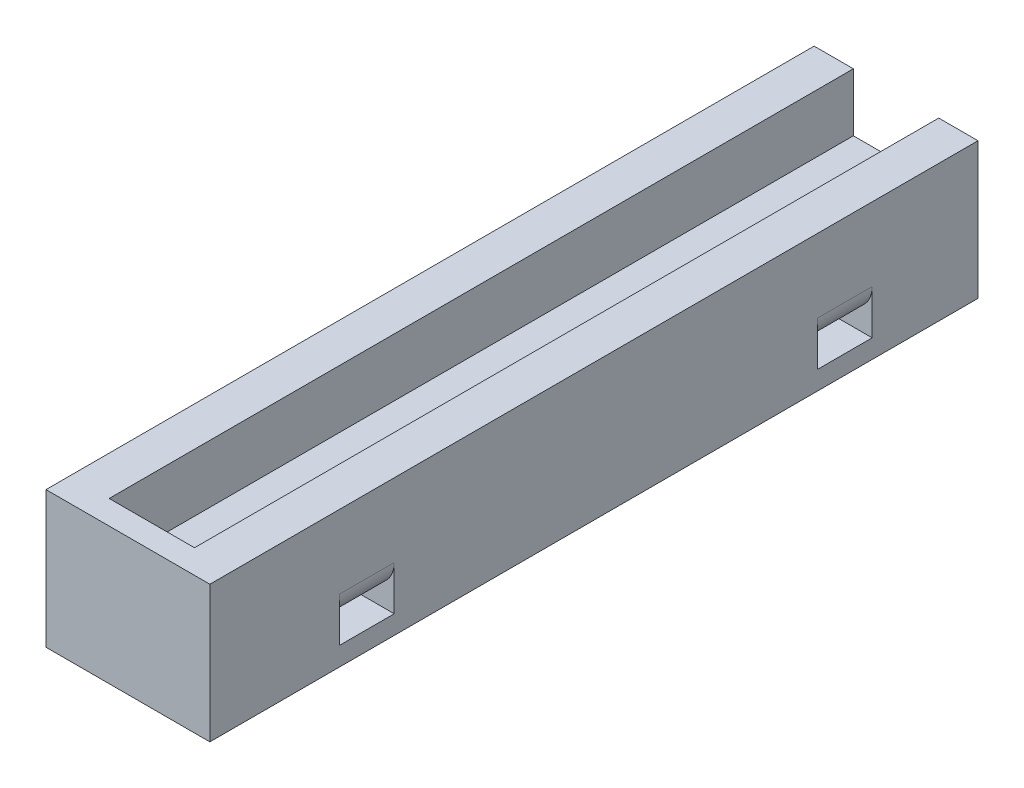
SolidWorks part; units mm, degrees
material "PLA"
ref_plane "Front Plane" through (0, 0, 0) normal (0, 0, 1) x (1, 0, 0)
ref_plane "Top Plane" through (0, 0, 0) normal (0, 1, 0) x (1, 0, 0)
ref_plane "Right Plane" through (0, 0, 0) normal (1, 0, 0) x (0, 0, -1)
sketch "Sketch1" plane through (0, 0, 0) normal (0, 0, 1) x (1, 0, 0)
  line L0 (-36, 5.6) -> (-26, 5.6) construction
  line L1 (-31, 5.6) -> (-31, 5.75) construction
  line L2 (0, 0) -> (-320, 0) construction
  line L3 (-37.25, 11.5) -> (-24.75, 11.5)
  line L4 (-37.25, 11.5) -> (-37.25, 0)
  line L5 (-37.25, 0) -> (-24.75, 0)
  line L6 (-24.75, 11.5) -> (-24.75, 0)
  line L7 (-37.25, 11.5) -> (-24.75, 0) construction
  line L8 (-37.25, 0) -> (-24.75, 11.5) construction
  line L10 (-24.75, 0) -> (-19, 0)
  line L11 (-24.75, 0) -> (-24.75, 20)
  line L12 (-24.75, 20) -> (-19, 20)
  line L13 (-19, 0) -> (-19, 20)
  line L14 (-37.25, 0) -> (-43, 0)
  line L15 (-37.25, 0) -> (-37.25, 20)
  line L16 (-37.25, 20) -> (-43, 20)
  line L17 (-43, 0) -> (-43, 20)
  dimension "D1" = 24
  dimension "D2" = 12.5
  dimension "D3" = 11.5
  dimension "D4" = 20
extrude "Boss-Extrude1" add sketch "Sketch1" along normal blind 109 contours L17 L14 L4 L15 L16 | L6 L3 L4 L5 | L10 L13 L12 L11 L6
sketch "Sketch2" plane through (0, 0, 109) normal (0, 0, 1) x (1, 0, 0)
  line L1 (-43, 20) -> (-19, 20)
  line L2 (-43, 20) -> (-43, 0)
  line L3 (-43, 0) -> (-19, 0)
  line L4 (-19, 20) -> (-19, 0)
extrude "Boss-Extrude2" add sketch "Sketch2" along normal blind 3.5
sketch "Sketch3" plane through (0, 0, 0) normal (0, 0, -1) x (-1, 0, 0)
  circle A0 centre (26, 5.6) radius 1.45 construction
  circle A1 centre (26, 5.6) radius 1.45 construction
  circle A2 centre (36, 5.6) radius 1.45 construction
  circle A3 centre (36, 5.6) radius 1.45 construction
  point P7 (26, 5.6)
  point P8 (36, 5.6)
hole_wizard "Ø2.5mm Dowel Hole1" positions "Sketch3" profile "Sketch4" hole size "Ø2.5" standard "ANSI Metric"
sketch "Sketch4" plane through (-36, 5.6, 0) normal (1, 0, 0) x (0, 1, 0)
  line L0 (0, 0) -> (0, 7.4614)
  line L1 (0, 7.4614) -> (1.6, 6.5)
  line L2 (1.6, 6.5) -> (1.6, 0)
  line L5 (1.6, 0) -> (0, 0)
  line L10 (0, 7.4614) -> (-1.6, 6.5) construction
  line L11 (0, -6.35) -> (0, 107.95) construction
  dimension "Hole Dia." = 3.2
  dimension "Hole Depth" = 6.5
  dimension "Drill Angle" = 118
sketch "Sketch5" plane through (-19, 0, 0) normal (1, 0, 0) x (0, 0, -1)
  line L0 (-109, 11.5) -> (-109, 20) construction
  line L1 (-109, 0) -> (-109, 20) construction
  line L2 (-112.5, 0) -> (0, 0) construction
  line L4 (-109, 4) -> (-89.5, 4) construction
  line L5 (-89.5, 4) -> (-19.5, 4) construction
  line L6 (-19.5, 4) -> (0, 4) construction
  line L7 (0, 0) -> (0, 20) construction
  line L9 (-93.5, 2.75) -> (-85.5, 2.75)
  line L10 (-93.5, 2.75) -> (-93.5, 5.25)
  line L11 (-93.5, 5.25) -> (-85.5, 5.25)
  line L12 (-85.5, 2.75) -> (-85.5, 5.25)
  line L13 (-93.5, 2.75) -> (-85.5, 5.25) construction
  line L14 (-93.5, 5.25) -> (-85.5, 2.75) construction
  line L15 (-15.5, 2.75) -> (-23.5, 2.75)
  line L16 (-15.5, 2.75) -> (-15.5, 5.25)
  line L17 (-15.5, 5.25) -> (-23.5, 5.25)
  line L18 (-23.5, 2.75) -> (-23.5, 5.25)
  line L19 (-15.5, 2.75) -> (-23.5, 5.25) construction
  line L20 (-15.5, 5.25) -> (-23.5, 2.75) construction
  dimension "D1" = 70
  dimension "D2" = 4
  dimension "D3" = 2.5
  dimension "D4" = 8
extrude "Cut-Extrude1" cut sketch "Sketch5" against normal through all
fillet "Fillet1" radius 4 4 edges at (-43, 5.25, 19.5) (-43, 5.25, 89.5) (-19, 5.25, 19.5) (-19, 5.25, 89.5)
